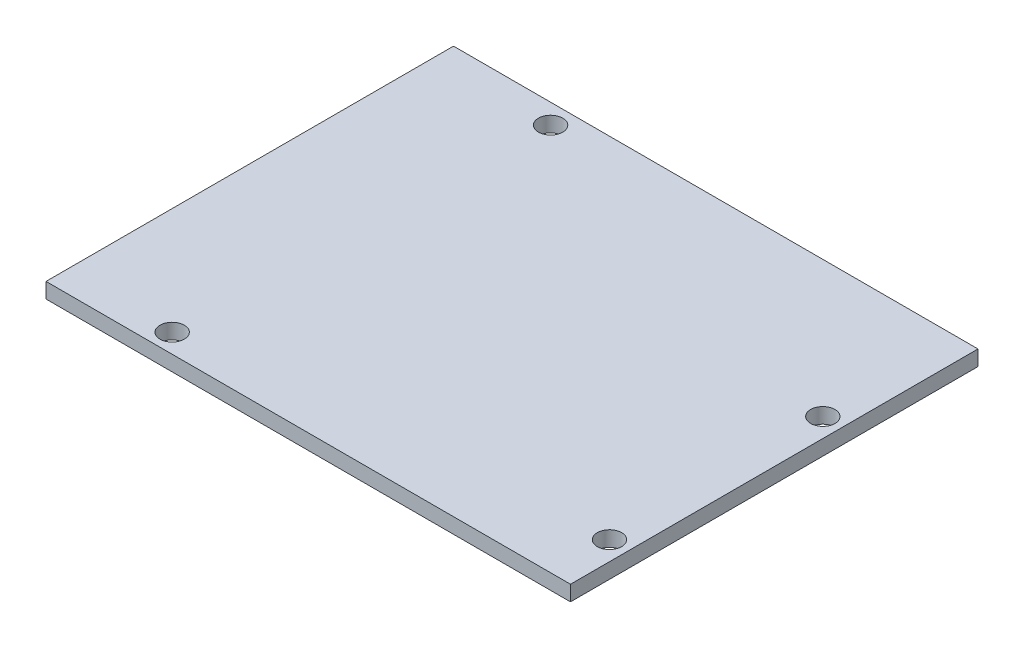
SolidWorks part; units mm, degrees
ref_plane "前视基准面" through (0, 0, 0) normal (0, 0, 1) x (1, 0, 0)
ref_plane "上视基准面" through (0, 0, 0) normal (0, 1, 0) x (1, 0, 0)
ref_plane "右视基准面" through (0, 0, 0) normal (1, 0, 0) x (0, 0, -1)
sketch "Sketch1" plane through (0, 0, 0) normal (0, 1, 0) x (1, 0, 0)
  line L1 (-34.3, 26.65) -> (34.3, 26.65)
  line L2 (-34.3, 26.65) -> (-34.3, -26.65)
  line L3 (-34.3, -26.65) -> (34.3, -26.65)
  line L4 (34.3, 26.65) -> (34.3, -26.65)
  circle A0 centre (-20.3, -24.15) radius 1.59
  circle A1 centre (-19, 24.05) radius 1.59
  circle A2 centre (31.8, 8.85) radius 1.59
  circle A3 centre (31.8, -19.05) radius 1.59
  point P0 (0, 0)
  dimension "D3" = 3.18
  dimension "D4" = 3.18
  dimension "D5" = 3.18
  dimension "D6" = 3.18
  dimension "D1" = 68.6
  dimension "D2" = 53.3
  dimension "D7" = 14
  dimension "D8" = 2.5
  dimension "D9" = 1.3
  dimension "D10" = 5.1
  dimension "D11" = 27.9
  dimension "D12" = 15.2
  dimension "D13" = 50.8
extrude "Boss-Extrude1" add sketch "Sketch1" along normal blind 2
